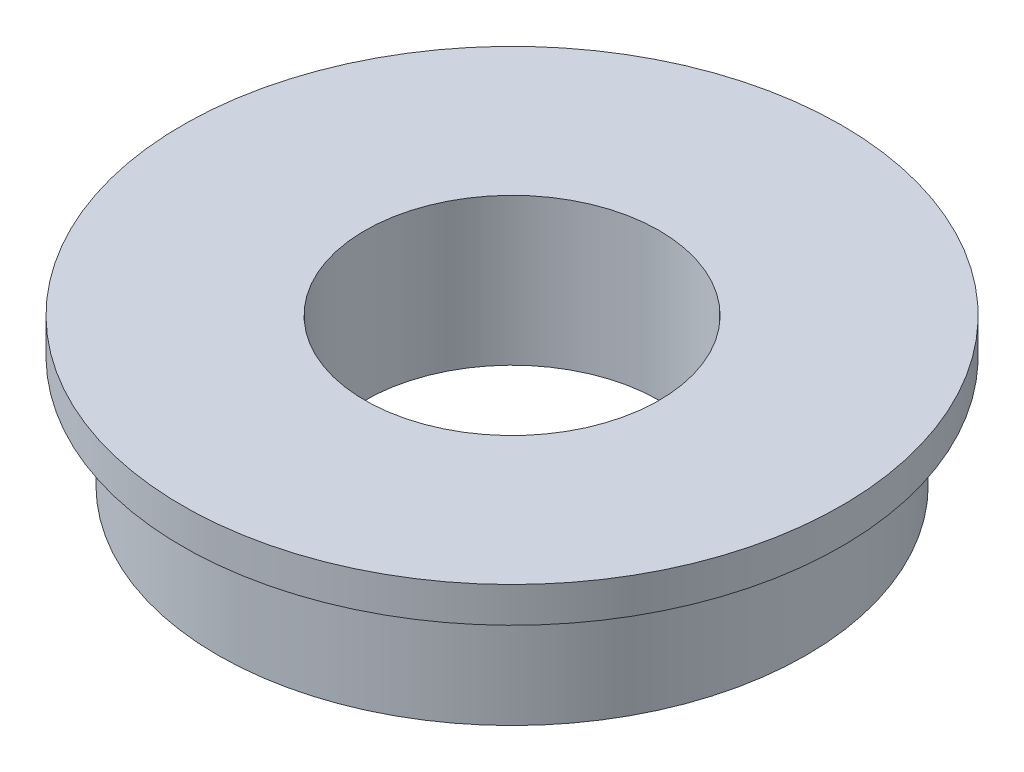
SolidWorks part; units mm, degrees
ref_plane "Front Plane" through (0, 0, 0) normal (0, 0, 1) x (1, 0, 0)
ref_plane "Top Plane" through (0, 0, 0) normal (0, 1, 0) x (1, 0, 0)
ref_plane "Right Plane" through (0, 0, 0) normal (1, 0, 0) x (0, 0, -1)
sketch "Sketch1" plane through (0, 0, 0) normal (0, 0, 1) x (1, 0, 0)
  line L0 (-3.175, 0) -> (-6.35, 0)
  line L1 (-6.35, 0) -> (-6.35, 2.413)
  line L2 (-6.35, 2.413) -> (-7.112, 2.413)
  line L3 (-7.112, 2.413) -> (-7.112, 3.175)
  line L4 (-7.112, 3.175) -> (-3.175, 3.175)
  line L5 (-3.175, 3.175) -> (-3.175, 0)
  dimension "D1" = 6.35
  dimension "D2" = 3.175
  dimension "D3" = 3.175
  dimension "D5" = 0.762
ref_axis "Axis1" through (0, -0.1588, 0) along (0, 1, 0)
revolve "Revolve1" add sketch "Sketch1" angle 360 about axis through (0, -0.1588, 0) along (0, 1, 0)
